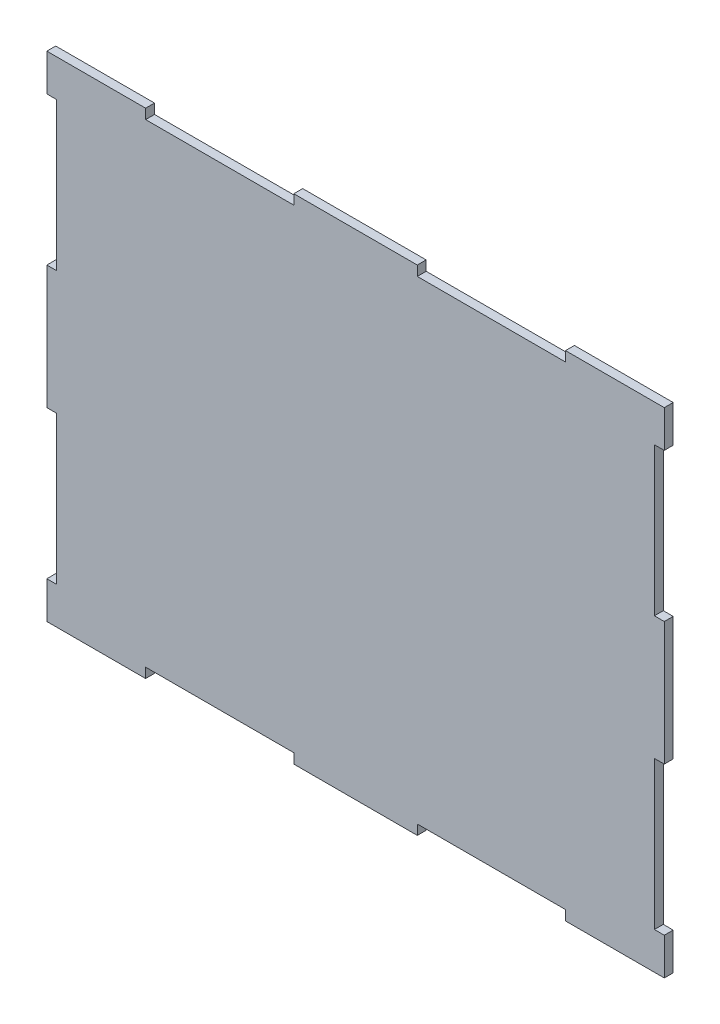
SolidWorks part; units mm, degrees
material "处理板，复杂型"
ref_plane "前视基准面" through (0, 0, 0) normal (0, 0, 1) x (1, 0, 0)
ref_plane "上视基准面" through (0, 0, 0) normal (0, 1, 0) x (1, 0, 0)
ref_plane "右视基准面" through (0, 0, 0) normal (1, 0, 0) x (0, 0, -1)
sketch "草图1" plane through (0, 0, 0) normal (0, 0, 1) x (1, 0, 0)
  line L0 (0, 389.8515) -> (0, -422.5248) construction
  line L1 (-125, 100) -> (125, 100)
  line L2 (-125, 100) -> (-125, -100)
  line L3 (-125, -100) -> (125, -100)
  line L4 (125, 100) -> (125, -100)
  dimension "D1" = 200
  dimension "D2" = 250
  dimension "D3" = 125
  dimension "D4" = 100
extrude "凸台-拉伸1" add sketch "草图1" along normal blind 3.6
sketch "草图2" plane through (0, 0, 3.6) normal (0, 0, 1) x (1, 0, 0)
  line L0 (-187.3662, 0) -> (197.8774, 0) construction
  line L1 (0, 153.4979) -> (0, -170.9485) construction
  line L2 (-121, 85) -> (-121, 25)
  line L5 (125, 85) -> (121, 85)
  line L6 (-125, 100) -> (-125, -100) construction
  line L7 (-125, 25) -> (-121, 25)
  line L9 (-125, -25) -> (-121, -25)
  line L11 (-125, 85) -> (-125, 25)
  line L12 (-125, -85) -> (-121, -85)
  line L16 (-125, 85) -> (-121, 85)
  line L20 (-121, -25) -> (-121, -85)
  line L21 (-125, -25) -> (-125, -85)
  line L22 (125, 85) -> (125, 25)
  line L23 (125, 25) -> (121, 25)
  line L24 (121, 85) -> (121, 25)
  line L25 (125, -25) -> (121, -25)
  line L26 (121, -25) -> (121, -85)
  line L27 (125, -85) -> (121, -85)
  line L28 (125, -25) -> (125, -85)
  dimension "D1" = 4
  dimension "D2" = 50
  dimension "D4" = 25
  dimension "D5" = 60
  dimension "D6" = 60
extrude "切除-拉伸1" cut sketch "草图2" against normal blind 10
sketch "草图3" plane through (0, 0, 3.6) normal (0, 0, 1) x (1, 0, 0)
  line L0 (-85, -96) -> (-25, -96)
  line L1 (0, 179.8057) -> (0, -208.2401) construction
  line L2 (-172.2789, 0) -> (195.6955, 0) construction
  line L4 (-125, -100) -> (125, -100) construction
  line L5 (25, -96) -> (85, -96)
  line L7 (-25, -96) -> (-25, -100)
  line L9 (25, -96) -> (25, -100)
  line L13 (-85, -96) -> (-85, -100)
  line L15 (85, -96) -> (85, -100)
  line L18 (-85, -100) -> (-25, -100)
  line L19 (25, -100) -> (85, -100)
  line L20 (25, 96) -> (25, 100)
  line L21 (25, 96) -> (85, 96)
  line L22 (85, 96) -> (85, 100)
  line L23 (25, 100) -> (85, 100)
  line L24 (-85, 96) -> (-85, 100)
  line L25 (-85, 96) -> (-25, 96)
  line L26 (-25, 96) -> (-25, 100)
  line L27 (-85, 100) -> (-25, 100)
  dimension "D1" = 4
  dimension "D2" = 50
  dimension "D5" = 25
  dimension "D6" = 60
  dimension "D7" = 60
extrude "切除-拉伸2" cut sketch "草图3" against normal blind 10
